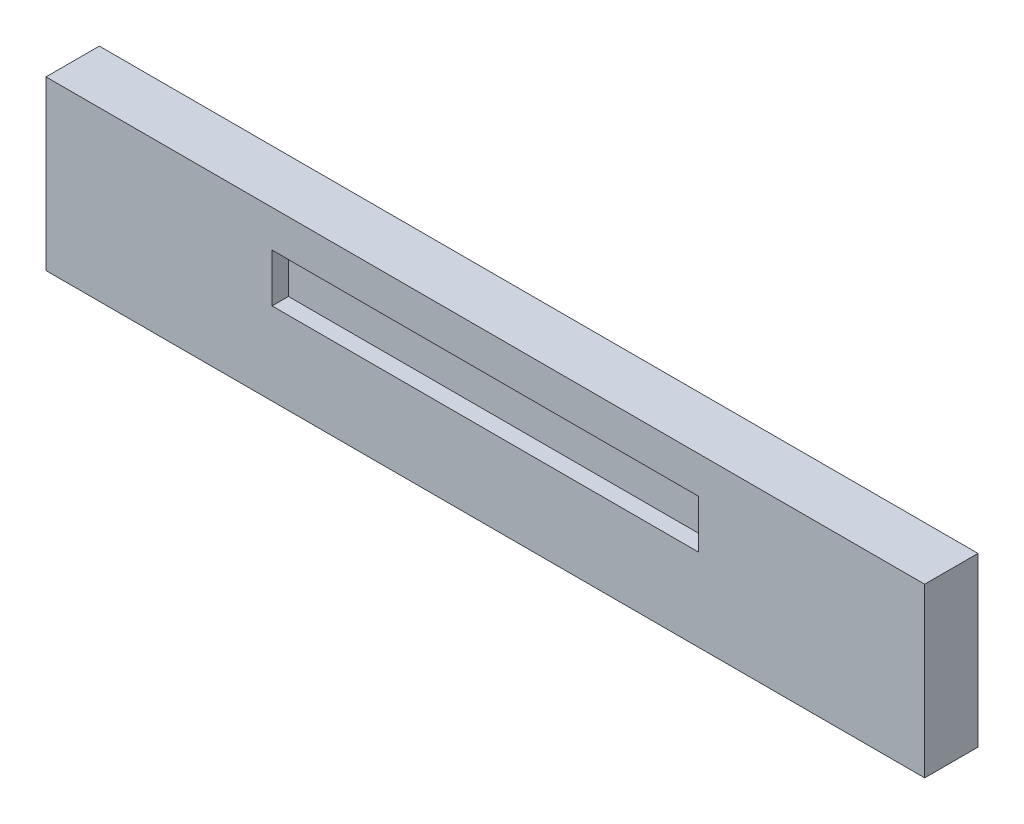
SolidWorks part; units mm, degrees
ref_plane "Front Plane" through (0, 0, 0) normal (0, 0, 1) x (1, 0, 0)
ref_plane "Top Plane" through (0, 0, 0) normal (0, 1, 0) x (1, 0, 0)
ref_plane "Right Plane" through (0, 0, 0) normal (1, 0, 0) x (0, 0, -1)
other "Configuration Table"
sketch "Sketch1" plane through (0, 0, 0) normal (0, 0, 1) x (1, 0, 0)
  line L1 (0, 0) -> (618, 0)
  line L2 (0, 0) -> (0, 118)
  line L3 (0, 118) -> (618, 118)
  line L4 (618, 0) -> (618, 118)
extrude "CEK_icecek_on_pu_37.5_1" add sketch "Sketch1" along normal blind 37.5 from offset 1 separate body
sketch "Sketch2" plane through (0, 0, 0) normal (0, 0, 1) x (1, 0, 0)
  line L1 (159, 58) -> (459, 58)
  line L2 (159, 58) -> (159, 92)
  line L3 (159, 92) -> (459, 92)
  line L4 (459, 58) -> (459, 92)
extrude "CEK_icecek_on_pu_37.5_2" cut sketch "Sketch2" along normal blind 14 from offset 27
